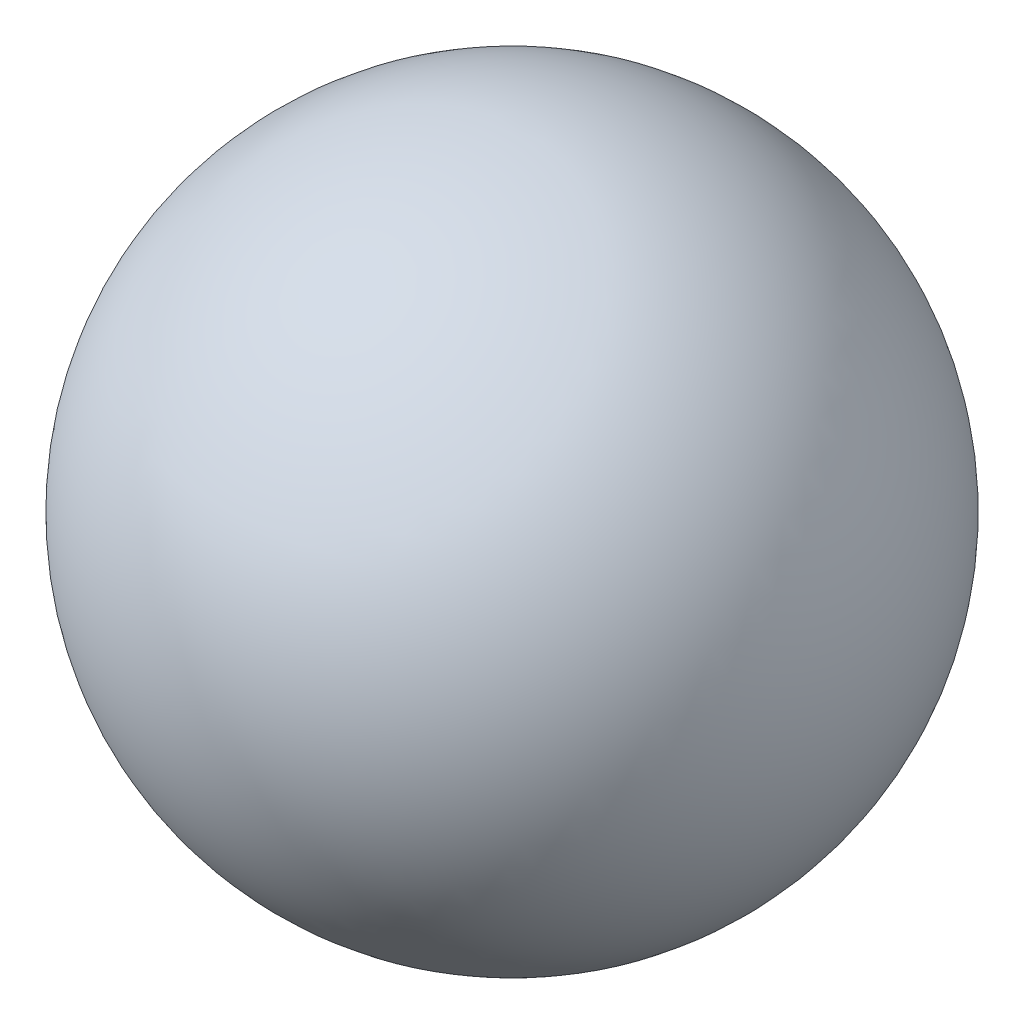
SolidWorks part; units mm, degrees
ref_plane "Front Plane" through (0, 0, 0) normal (0, 0, 1) x (1, 0, 0)
ref_plane "Top Plane" through (0, 0, 0) normal (0, 1, 0) x (1, 0, 0)
ref_plane "Right Plane" through (0, 0, 0) normal (1, 0, 0) x (0, 0, -1)
sketch "Sketch1" plane through (0, 0, 0) normal (0, 0, 1) x (1, 0, 0)
  line L0 (0, 19.05) -> (0, -19.05)
  arc A1 (0, 19.05) -> (0, -19.05) centre (0, 0) ccw
  dimension "D1" = 38.1
revolve "Revolve3" add sketch "Sketch1" angle 360 about L0
